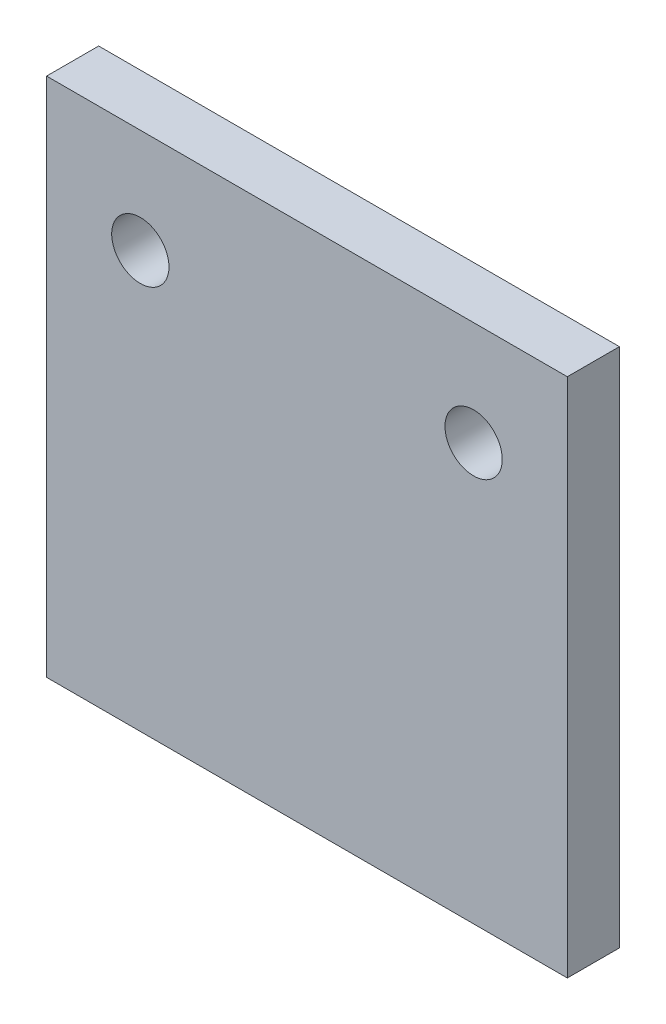
SolidWorks part; units mm, degrees
ref_plane "정면" through (0, 0, 0) normal (0, 0, 1) x (1, 0, 0)
ref_plane "윗면" through (0, 0, 0) normal (0, 1, 0) x (1, 0, 0)
ref_plane "우측면" through (0, 0, 0) normal (1, 0, 0) x (0, 0, -1)
sketch "스케치2" plane through (0, 0, 0) normal (0, 0, 1) x (1, 0, 0)
  line L1 (-25, 25) -> (25, 25)
  line L2 (-25, 25) -> (-25, -25)
  line L3 (-25, -25) -> (25, -25)
  line L4 (25, 25) -> (25, -25)
  line L5 (-25, 25) -> (25, -25) construction
  line L6 (-25, -25) -> (25, 25) construction
  point P0 (0, 0)
  dimension "D1" = 50
  dimension "D2" = 50
extrude "보스-돌출1" add sketch "스케치2" along normal blind 5
sketch "스케치3" plane through (0, 0, 5) normal (0, 0, 1) x (1, 0, 0)
  line L0 (-25, 25) -> (-25, -25) construction
  line L1 (25, 25) -> (-25, 25) construction
  circle A0 centre (-16, 15) radius 2.75
  circle A1 centre (16, 15) radius 2.75
  dimension "D1" = 5.5
  dimension "D2" = 5.5
  dimension "D3" = 9
  dimension "D4" = 41
  dimension "D5" = 10
  dimension "D6" = 10
extrude "컷-돌출1" cut sketch "스케치3" against normal blind 10
